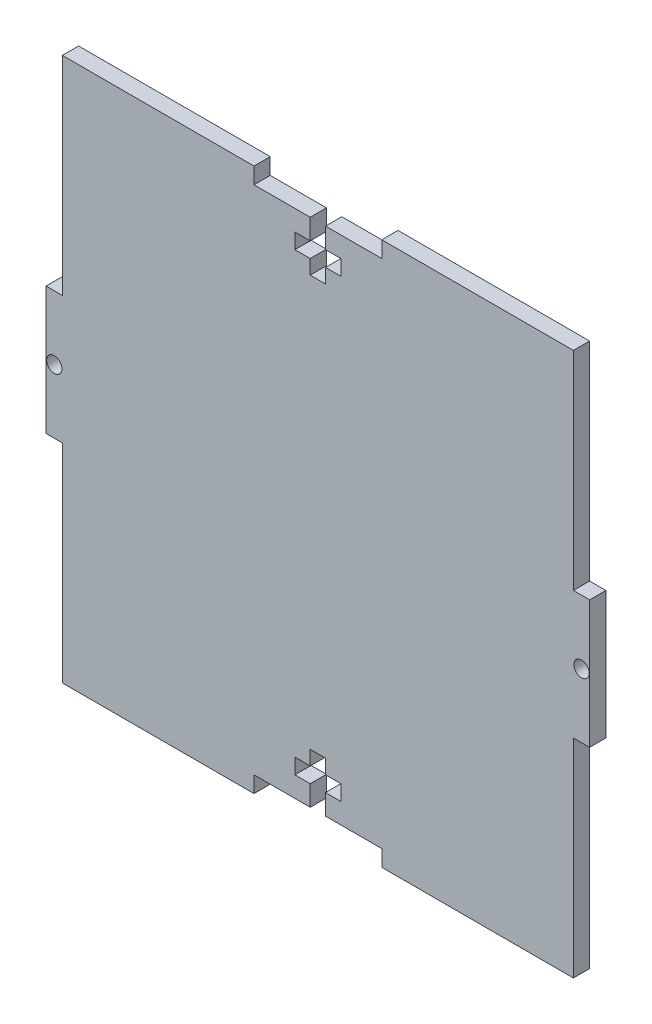
SolidWorks part; units mm, degrees
ref_plane "Front Plane" through (0, 0, 0) normal (0, 0, 1) x (1, 0, 0)
ref_plane "Top Plane" through (0, 0, 0) normal (0, 1, 0) x (1, 0, 0)
ref_plane "Right Plane" through (0, 0, 0) normal (1, 0, 0) x (0, 0, -1)
sketch "Sketch1" plane through (0, 0, 0) normal (0, 0, 1) x (1, 0, 0)
  line L0 (0, 50) -> (0, 53.18) construction
  line L1 (-50, 53.18) -> (-12.5, 53.18)
  line L2 (-50, 53.18) -> (-50, 12.5)
  line L3 (-50, -53.18) -> (-12.5, -53.18)
  line L4 (50, 53.18) -> (50, 12.5)
  line L5 (-50, 53.18) -> (50, -53.18) construction
  line L6 (-50, -53.18) -> (50, 53.18) construction
  line L7 (-12.5, 50) -> (-1.5, 50)
  line L8 (-12.5, 50) -> (-12.5, 53.18)
  line L10 (12.5, 50) -> (12.5, 53.18)
  line L11 (-12.5, 50) -> (12.5, 53.18) construction
  line L12 (-12.5, 53.18) -> (12.5, 50) construction
  line L13 (0, -53.18) -> (0, 53.18) construction
  line L14 (1.5, 50) -> (12.5, 50)
  line L15 (-1.5, 40.18) -> (1.5, 40.18)
  line L16 (-1.5, 40.18) -> (-1.5, 43)
  line L18 (1.5, 40.18) -> (1.5, 43)
  line L19 (-1.5, 40.18) -> (1.5, 50) construction
  line L20 (-1.5, 50) -> (1.5, 40.18) construction
  line L21 (-4.5, 46) -> (-1.5, 46)
  line L22 (-4.5, 46) -> (-4.5, 43)
  line L23 (-4.5, 43) -> (-1.5, 43)
  line L24 (4.5, 46) -> (4.5, 43)
  line L25 (-4.5, 46) -> (4.5, 43) construction
  line L26 (-4.5, 43) -> (4.5, 46) construction
  line L27 (-1.5, 46) -> (-1.5, 50)
  line L28 (1.5, 46) -> (4.5, 46)
  line L29 (1.5, 43) -> (4.5, 43)
  line L30 (1.5, 46) -> (1.5, 50)
  line L31 (-50, 0) -> (50, 0) construction
  line L32 (12.5, 53.18) -> (50, 53.18)
  line L33 (12.5, -50) -> (12.5, -53.18)
  line L34 (1.5, -50) -> (12.5, -50)
  line L35 (1.5, -46) -> (1.5, -50)
  line L36 (1.5, -46) -> (4.5, -46)
  line L37 (4.5, -46) -> (4.5, -43)
  line L38 (1.5, -43) -> (4.5, -43)
  line L39 (1.5, -40.18) -> (1.5, -43)
  line L40 (-1.5, -40.18) -> (1.5, -40.18)
  line L41 (-1.5, -40.18) -> (-1.5, -43)
  line L42 (-4.5, -43) -> (-1.5, -43)
  line L43 (-4.5, -46) -> (-4.5, -43)
  line L44 (-4.5, -46) -> (-1.5, -46)
  line L45 (-1.5, -46) -> (-1.5, -50)
  line L46 (-12.5, -50) -> (-1.5, -50)
  line L47 (-12.5, -50) -> (-12.5, -53.18)
  line L48 (12.5, -53.18) -> (50, -53.18)
  line L49 (-53.18, 0) -> (-50, 0) construction
  line L50 (-53.18, 12.5) -> (-50, 12.5)
  line L51 (-53.18, 12.5) -> (-53.18, -12.5)
  line L52 (-53.18, -12.5) -> (-50, -12.5)
  line L54 (-53.18, 12.5) -> (-50, -12.5) construction
  line L55 (-53.18, -12.5) -> (-50, 12.5) construction
  line L56 (-50, -12.5) -> (-50, -53.18)
  line L57 (53.18, -12.5) -> (50, -12.5)
  line L58 (53.18, 12.5) -> (53.18, -12.5)
  line L59 (53.18, 12.5) -> (50, 12.5)
  line L60 (50, -12.5) -> (50, -53.18)
  circle A0 centre (-51.59, 0) radius 1.5
  circle A1 centre (51.59, 0) radius 1.5
  point P0 (0, 0)
  point P6 (0, 51.59)
  point P14 (0, 45.09)
  point P19 (0, 44.5)
  point P46 (-51.59, 0)
  dimension "D12" = 3
  dimension "D1" = 106.36
  dimension "D2" = 100
  dimension "D3" = 25
  dimension "D4" = 3.18
  dimension "D5" = 3
  dimension "D6" = 13
  dimension "D7" = 3
  dimension "D8" = 4
  dimension "D9" = 9
  dimension "D10" = 25
  dimension "D11" = 3.18
extrude "Boss-Extrude1" add sketch "Sketch1" along normal blind 3.18
